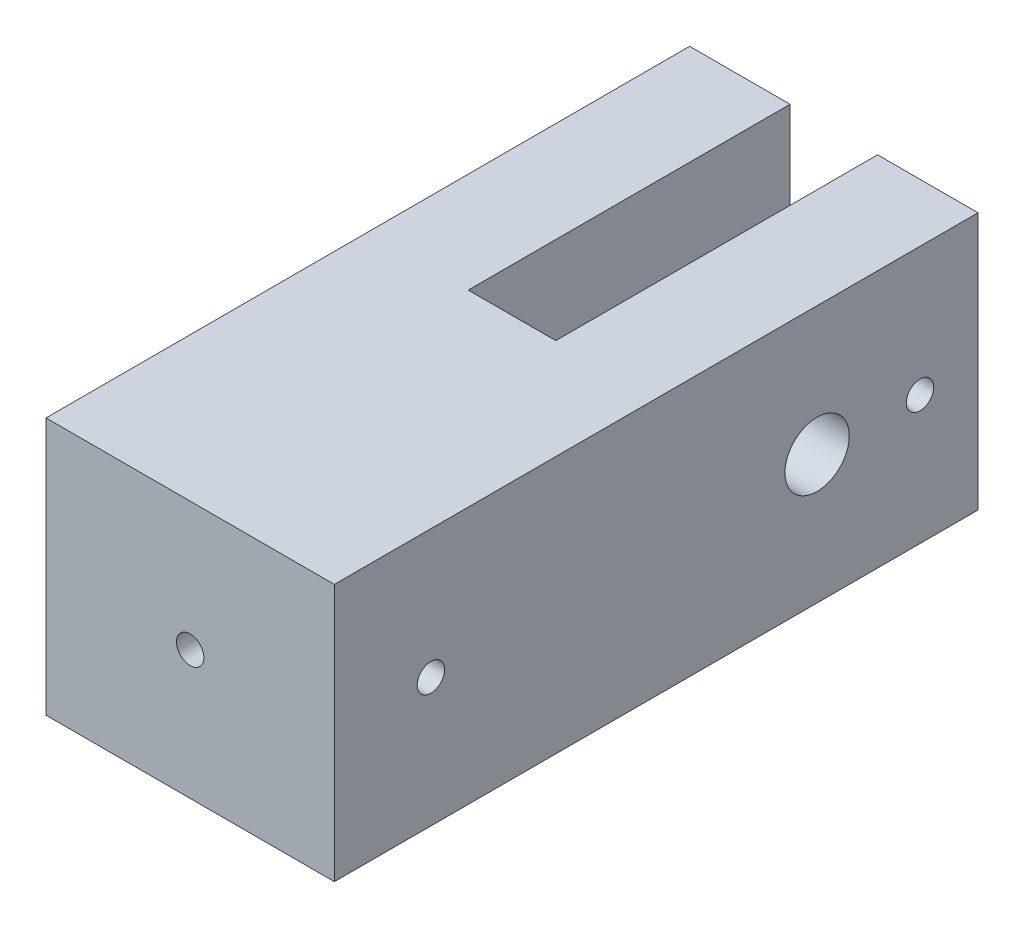
SolidWorks part; units mm, degrees
ref_plane "Front Plane" through (0, 0, 0) normal (0, 0, 1) x (1, 0, 0)
ref_plane "Top Plane" through (0, 0, 0) normal (0, 1, 0) x (1, 0, 0)
ref_plane "Right Plane" through (0, 0, 0) normal (1, 0, 0) x (0, 0, -1)
sketch "Sketch1" plane through (0, 0, 0) normal (0, 0, 1) x (1, 0, 0)
  line L1 (-14.224, 12.7) -> (14.224, 12.7)
  line L2 (-14.224, 12.7) -> (-14.224, -12.7)
  line L3 (-14.224, -12.7) -> (14.224, -12.7)
  line L4 (14.224, 12.7) -> (14.224, -12.7)
  line L5 (-14.224, 12.7) -> (14.224, -12.7) construction
  line L6 (-14.224, -12.7) -> (14.224, 12.7) construction
  point P0 (0, 0)
  dimension "D1" = 25.4
  dimension "D2" = 28.448
extrude "Boss-Extrude1" add sketch "Sketch1" along normal blind 63.5
sketch "Sketch2" plane through (0, 12.7, 0) normal (0, 1, 0) x (1, 0, 0)
  line L0 (0, 0) -> (0, -63.5) construction
  line L1 (14.224, -63.5) -> (-14.224, -63.5) construction
  line L2 (14.224, 0) -> (-14.224, 0) construction
  line L3 (-4.318, -31.75) -> (4.318, -31.75)
  line L4 (-4.318, -31.75) -> (-4.318, 0)
  line L5 (-4.318, 0) -> (4.318, 0)
  line L6 (4.318, -31.75) -> (4.318, 0)
  line L7 (-4.318, -31.75) -> (4.318, 0) construction
  line L8 (-4.318, 0) -> (4.318, -31.75) construction
  point P5 (0, -15.875)
  dimension "D1" = 8.636
  dimension "D2" = 31.75
extrude "Cut-Extrude1" cut sketch "Sketch2" against normal through all
sketch "Sketch3" plane through (-14.224, 0, 0) normal (-1, 0, 0) x (0, 0, 1)
  line L0 (0, 0) -> (63.5, 0) construction
  line L1 (63.5, 12.7) -> (63.5, -12.7) construction
  circle A0 centre (15.875, 0) radius 3.175
  dimension "D1" = 6.35
  dimension "D2" = 15.875
extrude "Cut-Extrude3" cut sketch "Sketch3" against normal through all
hole_wizard "#6-32 Tapped Hole1" positions "Sketch5" profile "Sketch6" tap size "#6-32" standard "ANSI Inch"
sketch "Sketch5" plane through (-14.224, 0, 0) normal (-1, 0, 0) x (0, 0, 1)
  line L0 (0, 0) -> (63.5, 0) construction
  line L1 (0, 12.7) -> (0, -12.7) construction
  line L2 (63.5, 12.7) -> (63.5, -12.7) construction
  circle A0 centre (15.875, 0) radius 3.175 construction
  point P8 (5.715, 0)
  point P10 (53.975, 0)
  dimension "D1" = 10.16
  dimension "D2" = 38.1
cosmetic thread "Hole Thread1" parameters "D2"=3.5052
cosmetic thread "Hole Thread2" parameters "D2"=3.5052
sketch "Sketch6" plane through (-14.224, 0, 5.715) normal (0, 1, 0) x (0, 0, 1)
  line L0 (0, 0) -> (0, 7.1627)
  line L1 (0, 7.1627) -> (1.3525, 6.35)
  line L2 (1.3525, 6.35) -> (1.3525, 0)
  line L5 (1.3525, 0) -> (0, 0)
  line L10 (0, 7.1627) -> (-1.3526, 6.35) construction
  line L11 (0, -6.35) -> (0, 107.95) construction
  dimension "Tap Drill Dia." = 2.7051
  dimension "Tap Drill Depth" = 6.35
  dimension "Drill Angle" = 118
hole_wizard "#6-32 Tapped Hole2" positions "Sketch8" profile "Sketch9" tap size "#6-32" standard "ANSI Inch"
sketch "Sketch8" plane through (14.224, 0, 0) normal (1, 0, 0) x (0, 0, -1)
  line L0 (-63.5, 0) -> (0, 0) construction
  line L1 (-63.5, -12.7) -> (-63.5, 12.7) construction
  line L2 (0, -12.7) -> (0, 12.7) construction
  circle A0 centre (-15.875, 0) radius 3.175 construction
  point P9 (-53.975, 0)
  point P11 (-5.715, 0)
  dimension "D1" = 10.16
  dimension "D2" = 38.1
cosmetic thread "Hole Thread3" parameters "D2"=3.5052
cosmetic thread "Hole Thread5" parameters "D2"=3.5052
sketch "Sketch9" plane through (14.224, 0, 53.975) normal (0, 1, 0) x (0, 0, -1)
  line L0 (0, 0) -> (0, 7.1627)
  line L1 (0, 7.1627) -> (1.3525, 6.35)
  line L2 (1.3525, 6.35) -> (1.3525, 0)
  line L5 (1.3525, 0) -> (0, 0)
  line L10 (0, 7.1627) -> (-1.3526, 6.35) construction
  line L11 (0, -6.35) -> (0, 107.95) construction
  dimension "Tap Drill Dia." = 2.7051
  dimension "Tap Drill Depth" = 6.35
  dimension "Drill Angle" = 118
hole_wizard "#6-32 Tapped Hole3" positions "Sketch13" profile "Sketch14" tap size "#6-32" standard "ANSI Inch" end condition through all
sketch "Sketch13" plane through (0, 0, 31.75) normal (0, 0, -1) x (-1, 0, 0)
  point P0 (0, 0)
sketch "Sketch14" plane through (0, 0, 31.75) normal (1, 0, 0) x (0, 1, 0)
  line L0 (0, 0) -> (0, 31.75)
  line L1 (0, 31.75) -> (1.3525, 31.75)
  line L2 (1.3525, 31.75) -> (1.3525, 0)
  line L5 (1.3525, 0) -> (0, 0)
  line L11 (0, -6.35) -> (0, 107.95) construction
  dimension "Thru Tap Drill Dia." = 2.7051
  dimension "Thru Tap Drill Depth" = 31.75
cosmetic thread "Hole Thread6" parameters "D2"=3.5052
sketch "Sketch15" plane through (0, 0, 31.75) normal (0, 0, -1) x (-1, 0, 0)
  circle A0 centre (0, 0) radius 3.175
  dimension "D1" = 6.35
extrude "Cut-Extrude4" [suppressed] cut sketch "Sketch15" against normal blind 3.556
